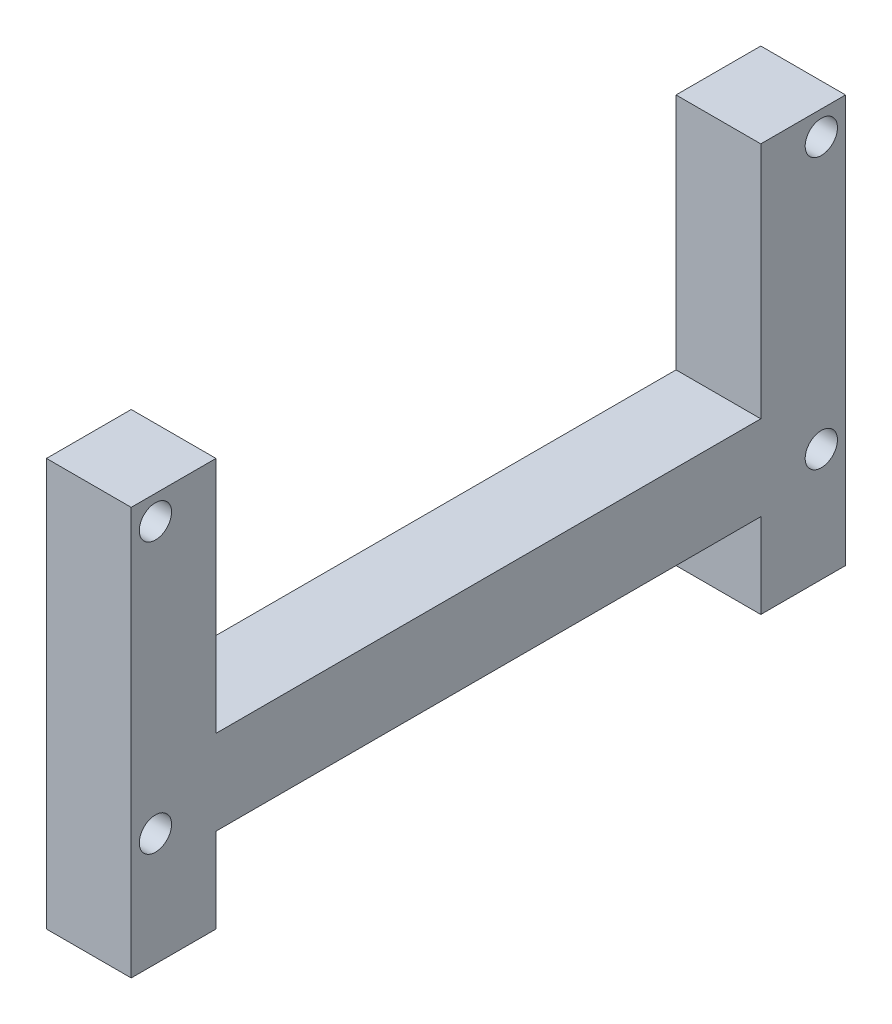
SolidWorks part; units mm, degrees
ref_plane "Front Plane" through (0, 0, 0) normal (0, 0, 1) x (1, 0, 0)
ref_plane "Top Plane" through (0, 0, 0) normal (0, 1, 0) x (1, 0, 0)
ref_plane "Right Plane" through (0, 0, 0) normal (1, 0, 0) x (0, 0, -1)
sketch "Sketch1" plane through (0, 0, 0) normal (1, 0, 0) x (0, 0, -1)
  line L0 (5.334, 0) -> (5.334, 20.32)
  line L1 (0, 0) -> (44.958, 0)
  line L2 (0, 0) -> (0, 25.654)
  line L3 (0, 25.654) -> (44.958, 25.654)
  line L4 (44.958, 0) -> (44.958, 25.654)
  line L5 (5.334, 20.32) -> (39.624, 20.32)
  line L6 (39.624, 20.32) -> (39.624, 0)
  line L7 (0, 5.334) -> (5.334, 5.334)
  line L8 (39.624, 5.334) -> (44.958, 5.334)
  line L9 (5.334, 5.334) -> (39.624, 5.334)
  line L10 (5.334, 10.668) -> (39.624, 10.668)
  line L11 (22.479, 25.654) -> (22.479, 13.1837) construction
  line L12 (15.494, 5.334) -> (15.494, 10.668)
  line L13 (29.464, 5.334) -> (29.464, 10.668)
  line L14 (5.334, 20.32) -> (5.334, 25.654)
  line L15 (39.624, 20.32) -> (39.624, 25.654)
  circle A0 centre (1.524, 24.13) radius 1.016
  circle A1 centre (1.524, 7.112) radius 1.016
  circle A2 centre (43.434, 7.112) radius 1.016
  circle A3 centre (43.434, 24.13) radius 1.016
  dimension "D6" = 2.032
  dimension "D11" = 2.032
  dimension "D1" = 5.334
  dimension "D2" = 5.334
  dimension "D3" = 5.334
  dimension "D4" = 44.958
  dimension "D5" = 25.654
  dimension "D7" = 1.524
  dimension "D8" = 1.524
  dimension "D10" = 5.334
  dimension "D12" = 1.524
  dimension "D9" = 17.018
  dimension "D13" = 5.334
  dimension "D14" = 10.16
  dimension "D15" = 10.16
extrude "Boss-Extrude1" add sketch "Sketch1" along normal blind 5.334 contours L7 L2 L1 L0 | L11 L3 L2 L7 L0 L5 A1 A0 | L3 L11 L5 L6 L8 L4 A3 A2 | L8 L6 L1 L4 | L9 L12 L10 L0 | L13 L9 L6 L10 | L9 L13 L10 L12
equation "\"material_thickness\"= 0.21"
equation "\"D1@Sketch1\"=\"material_thickness\""
equation "\"D2@Sketch1\"=\"material_thickness\""
equation "\"D3@Sketch1\"=\"material_thickness\""
equation "\"D5@Sketch1\"=\"material_thickness\"+0.8"
equation "\"D10@Sketch1\"=\"material_thickness\""
equation "\"D13@Sketch1\"=\"material_thickness\""
equation "\"D1@Boss-Extrude1\"=\"material_thickness\""
